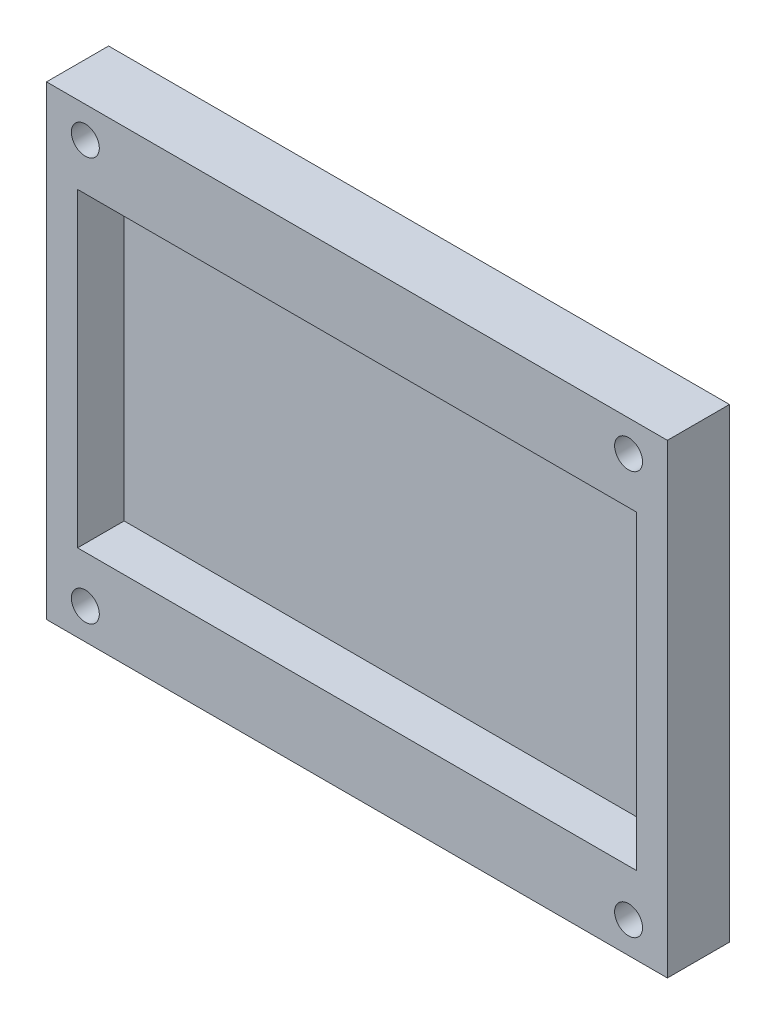
SolidWorks part; units mm, degrees
ref_plane "Front Plane" through (0, 0, 0) normal (0, 0, 1) x (1, 0, 0)
ref_plane "Top Plane" through (0, 0, 0) normal (0, 1, 0) x (1, 0, 0)
ref_plane "Right Plane" through (0, 0, 0) normal (1, 0, 0) x (0, 0, -1)
sketch "Sketch1" plane through (0, 0, 0) normal (0, 0, 1) x (1, 0, 0)
  line L1 (-20, -15) -> (20, -15)
  line L2 (-20, -15) -> (-20, 15)
  line L3 (-20, 15) -> (20, 15)
  line L4 (20, -15) -> (20, 15)
  line L5 (-20, -15) -> (20, 15) construction
  line L6 (-20, 15) -> (20, -15) construction
  point P0 (0, 0)
extrude "Boss-Extrude1" add sketch "Sketch1" along normal blind 4
sketch "Sketch2" plane through (0, 0, 0) normal (0, 0, 1) x (1, 0, 0)
  line L1 (-18, -10) -> (18, -10)
  line L2 (-18, -10) -> (-18, 10)
  line L3 (-18, 10) -> (18, 10)
  line L4 (18, -10) -> (18, 10)
  line L5 (-18, -10) -> (18, 10) construction
  line L6 (-18, 10) -> (18, -10) construction
  point P0 (0, 0)
extrude "Cut-Extrude1" cut sketch "Sketch2" against normal blind 3 from surface at 4 starting at face at (0, 0, 4)
sketch "Sketch3" plane through (0, 0, 0) normal (0, 0, 1) x (1, 0, 0)
  line L0 (-20, 15) -> (-20, 13) construction
  line L1 (-20, 15) -> (-20, -15) construction
  line L2 (-20, 13) -> (-17.5, 13) construction
  line L3 (0, 0) -> (0, 3.4555) construction
  line L4 (0, 0) -> (5.1328, 0) construction
  circle A0 centre (-17.5, 13) radius 0.9
  circle A1 centre (-17.5, -13) radius 0.9
  circle A2 centre (17.5, -13) radius 0.9
  circle A3 centre (17.5, 13) radius 0.9
extrude "Cut-Extrude2" cut sketch "Sketch3" against normal blind 13 from surface at 4 starting at face at (0, 0, 4)
